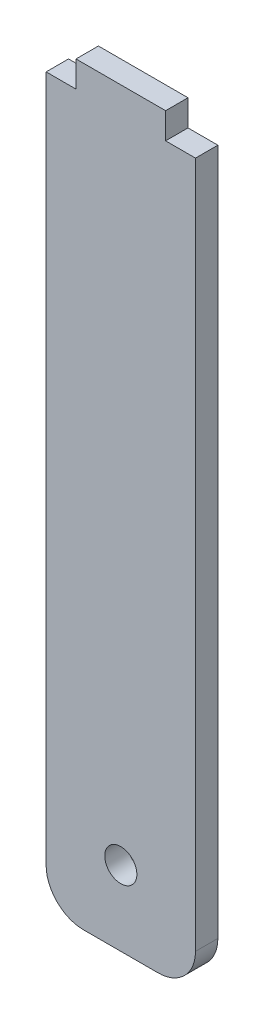
SolidWorks part; units mm, degrees
material "Thornel Mat VMA"
ref_plane "前视基准面" through (0, 0, 0) normal (0, 0, 1) x (1, 0, 0)
ref_plane "上视基准面" through (0, 0, 0) normal (0, 1, 0) x (1, 0, 0)
ref_plane "右视基准面" through (0, 0, 0) normal (1, 0, 0) x (0, 0, -1)
sketch "草图1" plane through (0, 0, 0) normal (0, 0, 1) x (1, 0, 0)
  line L0 (16, 97) -> (20, 97)
  line L1 (0, 0) -> (20, 0)
  line L2 (0, 0) -> (0, 97)
  line L3 (0, 97) -> (4, 97)
  line L4 (20, 0) -> (20, 97)
  line L6 (4, 97) -> (4, 100.5)
  line L7 (4, 100.5) -> (16, 100.5)
  line L8 (16, 97) -> (16, 100.5)
  line L9 (10, 100.5) -> (10, 87.711) construction
  circle A0 centre (10, 10) radius 2.15
  dimension "D5" = 4.3
  dimension "D6" = 10
  dimension "D1" = 3.5
  dimension "D2" = 12
  dimension "D3" = 20
  dimension "D4" = 97
extrude "凸台-拉伸1" add sketch "草图1" along normal blind 3
fillet "圆角1" radius 5 2 edges at (0, 0, 1.5) (20, 0, 1.5)
